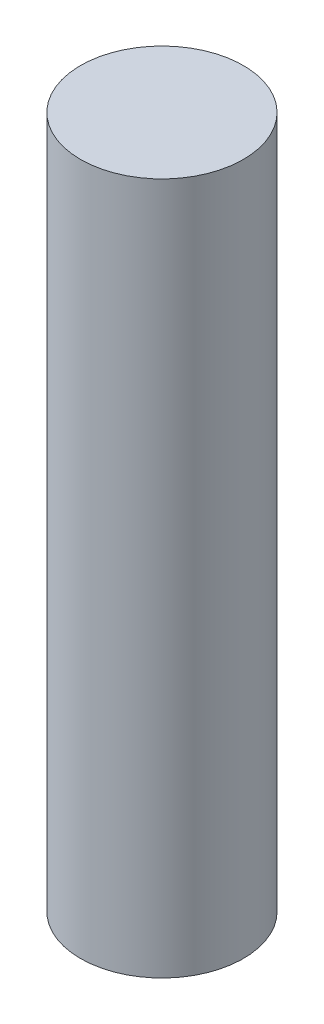
SolidWorks part; units mm, degrees
ref_plane "Front Plane" through (0, 0, 0) normal (0, 0, 1) x (1, 0, 0)
ref_plane "Top Plane" through (0, 0, 0) normal (0, 1, 0) x (1, 0, 0)
ref_plane "Right Plane" through (0, 0, 0) normal (1, 0, 0) x (0, 0, -1)
sketch "Sketch1" plane through (0, 0, 0) normal (0, 1, 0) x (1, 0, 0)
  circle A0 centre (0, 0) radius 10
extrude "Boss-Extrude1" add sketch "Sketch1" along normal blind 85
